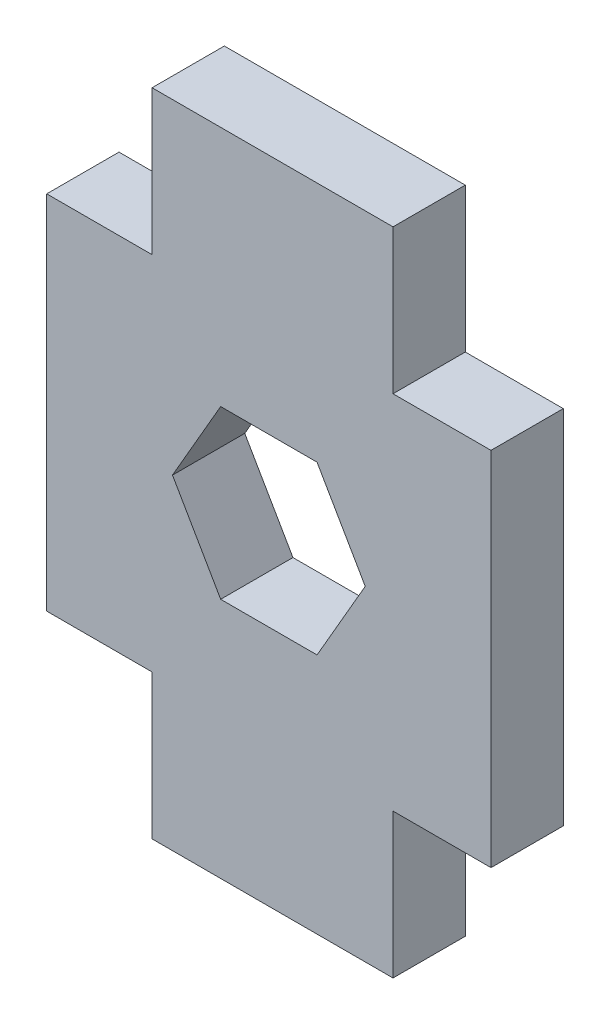
SolidWorks part; units mm, degrees
ref_plane "Front Plane" through (0, 0, 0) normal (0, 0, 1) x (1, 0, 0)
ref_plane "Top Plane" through (0, 0, 0) normal (0, 1, 0) x (1, 0, 0)
ref_plane "Right Plane" through (0, 0, 0) normal (1, 0, 0) x (0, 0, -1)
sketch "Sketch1" plane through (0, 0, 0) normal (0, 0, 1) x (1, 0, 0)
  line L2 (-211.4286, -77.263) -> (-211.4286, -107.263)
  line L4 (-174.5494, -77.263) -> (-174.5494, -107.263)
  line L6 (-202.6836, -71.263) -> (-202.6836, -65.263)
  line L7 (-202.6836, -65.263) -> (-182.6836, -65.263)
  line L8 (-182.6836, -71.263) -> (-182.6836, -65.263)
  line L14 (-211.4286, -77.263) -> (-202.6836, -77.263)
  line L16 (-202.6836, -71.263) -> (-202.6836, -77.263)
  line L18 (-182.6836, -71.263) -> (-182.6836, -77.263)
  line L19 (-182.6836, -77.263) -> (-174.5494, -77.263)
  line L21 (-182.6836, -107.263) -> (-174.5494, -107.263)
  line L22 (-182.6836, -113.263) -> (-182.6836, -107.263)
  line L23 (-202.6836, -113.263) -> (-202.6836, -107.263)
  line L24 (-211.4286, -107.263) -> (-202.6836, -107.263)
  line L25 (-182.6836, -113.263) -> (-182.6836, -119.263)
  line L26 (-202.6836, -119.263) -> (-182.6836, -119.263)
  line L27 (-202.6836, -113.263) -> (-202.6836, -119.263)
  line L29 (-184.989, -92.263) -> (-188.989, -85.3348)
  line L30 (-188.989, -85.3348) -> (-196.989, -85.3348)
  line L31 (-196.989, -85.3348) -> (-200.989, -92.263)
  line L32 (-200.989, -92.263) -> (-196.989, -99.1912)
  line L33 (-196.989, -99.1912) -> (-188.989, -99.1912)
  line L34 (-188.989, -99.1912) -> (-184.989, -92.263)
  circle A1 centre (-192.989, -92.263) radius 6.9282 construction
  dimension "D1" = 6
  dimension "D2" = 6
  dimension "D3" = 16
  dimension "D4" = 12
  dimension "D5" = 30
extrude "Boss-Extrude1" add sketch "Sketch1" along normal blind 6
